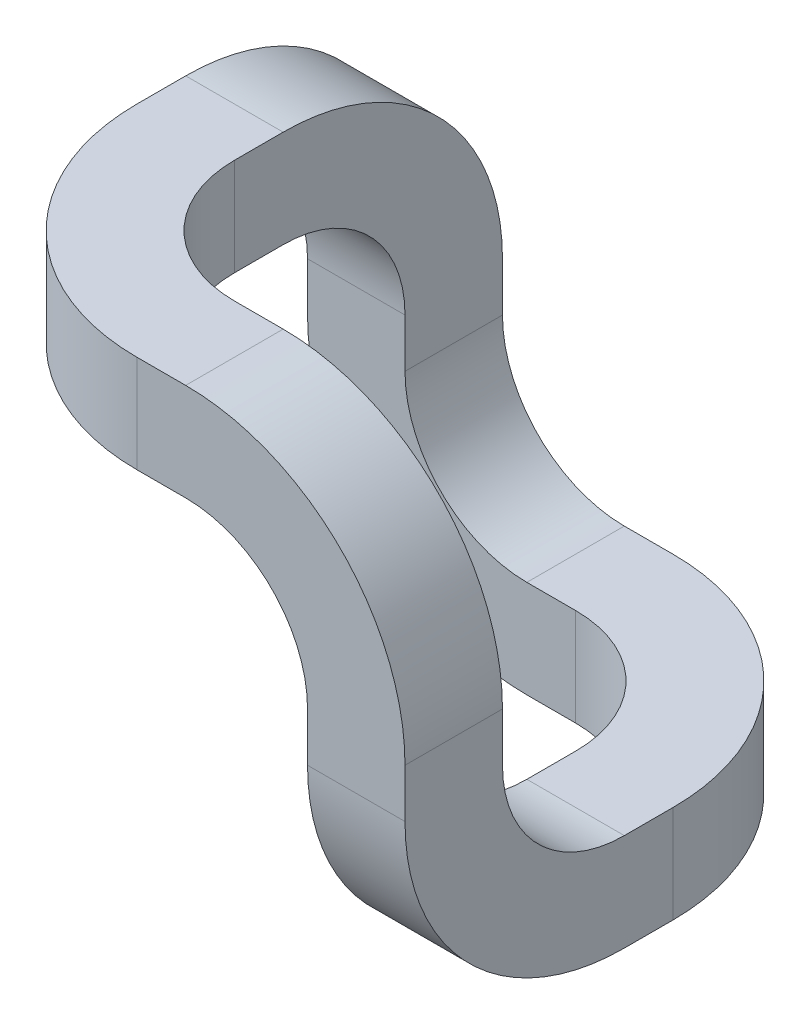
SolidWorks part; units mm, degrees
material "Brass"
ref_plane "Front Plane" through (0, 0, 0) normal (0, 0, 1) x (1, 0, 0)
ref_plane "Top Plane" through (0, 0, 0) normal (0, 1, 0) x (1, 0, 0)
ref_plane "Right Plane" through (0, 0, 0) normal (1, 0, 0) x (0, 0, -1)
sketch "Sketch1" plane through (0, 0, 0) normal (0, 0, 1) x (1, 0, 0)
  line L1 (0, 0) -> (20, 0)
  line L2 (0, 0) -> (0, 20)
  line L3 (0, 20) -> (20, 20)
  line L4 (20, 0) -> (20, 20)
  dimension "D1" = 20
  dimension "D2" = 20
extrude "Boss-Extrude1" add sketch "Sketch1" along normal mid plane 20
sketch "Sketch2" plane through (0, 0, 0) normal (0, 0, 1) x (1, 0, 0)
  line L0 (20, 20) -> (0, 20) construction
  line L1 (4, 4) -> (16, 4)
  line L2 (4, 4) -> (4, 16)
  line L3 (4, 16) -> (16, 16)
  line L4 (16, 4) -> (16, 16)
  line L5 (0, 20) -> (0, 0) construction
  line L6 (0, 0) -> (20, 0) construction
  line L7 (20, 0) -> (20, 20) construction
  dimension "D1" = 4
  dimension "D2" = 4
  dimension "D3" = 4
  dimension "D4" = 4
extrude "Cut-Extrude1" cut sketch "Sketch2" against normal mid plane 38
sketch "Sketch3" plane through (0, 0, 0) normal (0, 1, 0) x (1, 0, 0)
  line L0 (20, 10) -> (0, 10) construction
  line L1 (4, -6) -> (16, -6)
  line L2 (4, -6) -> (4, 6)
  line L3 (4, 6) -> (16, 6)
  line L4 (16, -6) -> (16, 6)
  line L5 (0, -10) -> (0, 10) construction
  line L6 (20, -10) -> (0, -10) construction
  line L7 (20, -10) -> (20, 10) construction
  dimension "D1" = 4
  dimension "D2" = 4
  dimension "D3" = 4
  dimension "D4" = 4
extrude "Cut-Extrude2" cut sketch "Sketch3" against normal mid plane 62
sketch "Sketch4" plane through (0, 0, 0) normal (1, 0, 0) x (0, 0, -1)
  line L0 (-10, 20) -> (10, 20) construction
  line L1 (-6, 4) -> (6, 4)
  line L2 (-6, 4) -> (-6, 16)
  line L3 (-6, 16) -> (6, 16)
  line L4 (6, 4) -> (6, 16)
  line L5 (10, 0) -> (10, 20) construction
  line L6 (-10, 0) -> (10, 0) construction
  line L7 (-10, 0) -> (-10, 20) construction
  dimension "D1" = 4
  dimension "D2" = 4
  dimension "D3" = 4
  dimension "D4" = 4
extrude "Cut-Extrude3" cut sketch "Sketch4" against normal mid plane 78
sketch "Sketch5" plane through (0, 0, 0) normal (0, 0, 1) x (1, 0, 0)
  line L1 (0, 16) -> (16, 16)
  line L2 (0, 16) -> (0, 0)
  line L3 (0, 0) -> (16, 0)
  line L4 (16, 16) -> (16, 0)
extrude "Cut-Extrude5" cut sketch "Sketch5" against normal blind 6 and the other way blind 21
sketch "Sketch6" plane through (0, 0, 0) normal (0, 1, 0) x (1, 0, 0)
  line L1 (4, -6) -> (21.4786, -6)
  line L2 (4, -6) -> (4, 12.2315)
  line L3 (4, 12.2315) -> (21.4786, 12.2315)
  line L4 (21.4786, -6) -> (21.4786, 12.2315)
extrude "Cut-Extrude8" cut sketch "Sketch6" along normal blind 43 from offset 4
fillet "Fillet3" radius 9 1 edges at (20, 20, 8)
fillet "Fillet4" radius 9 1 edges at (0, 0, -8)
fillet "Fillet5" radius 9 1 edges at (20, 2, -10)
fillet "Fillet6" radius 9 1 edges at (0, 18, 10)
fillet "Fillet7" radius 9 1 edges at (2, 20, -10)
fillet "Fillet8" radius 9 1 edges at (18, 0, 10)
fillet "Fillet9" radius 5 1 edges at (4, 18, 6)
fillet "Fillet10" radius 5 1 edges at (16, 2, -6)
fillet "Fillet11" radius 5 1 edges at (16, 16, 8)
fillet "Fillet12" radius 5 1 edges at (4, 4, -8)
fillet "Fillet13" radius 5 1 edges at (18, 4, 6)
fillet "Fillet14" radius 5 1 edges at (2, 16, -6)
